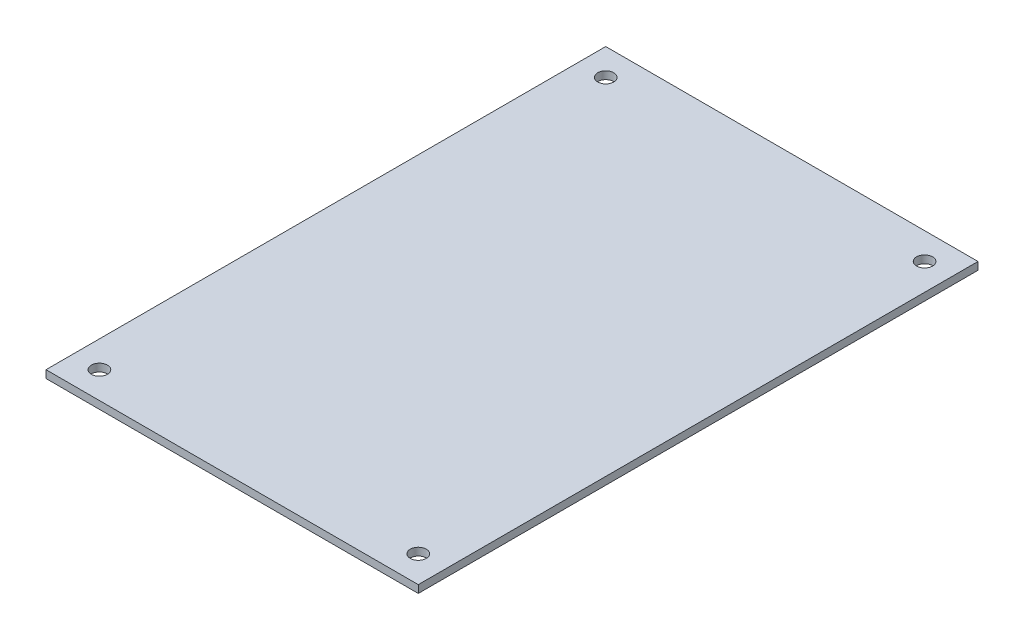
SolidWorks part; units mm, degrees
ref_plane "Front Plane" through (0, 0, 0) normal (0, 0, 1) x (1, 0, 0)
ref_plane "Top Plane" through (0, 0, 0) normal (0, 1, 0) x (1, 0, 0)
ref_plane "Right Plane" through (0, 0, 0) normal (1, 0, 0) x (0, 0, -1)
sketch "Sketch1" plane through (0, 0, 0) normal (0, 1, 0) x (1, 0, 0)
  line L1 (39.4716, -59.3471) -> (-39.4716, -59.3471)
  line L2 (39.4716, -59.3471) -> (39.4716, 59.3471)
  line L3 (39.4716, 59.3471) -> (-39.4716, 59.3471)
  line L4 (-39.4716, -59.3471) -> (-39.4716, 59.3471)
  line L5 (39.4716, -59.3471) -> (-39.4716, 59.3471) construction
  line L6 (39.4716, 59.3471) -> (-39.4716, -59.3471) construction
  point P0 (0, 0)
  dimension "D1" = 78.9432
  dimension "D2" = 118.6942
extrude "Boss-Extrude1" add sketch "Sketch1" along normal blind 1.6256
sketch "Sketch2" plane through (0, 1.6256, 0) normal (0, 1, 0) x (1, 0, 0)
  line L0 (-39.4716, 59.3471) -> (-39.4716, -59.3471) construction
  line L1 (39.4716, 59.3471) -> (-39.4716, 59.3471) construction
  circle A0 centre (-33.8074, 53.6829) radius 1.7018
  dimension "D1" = 3.4036
  dimension "D2" = 5.6642
  dimension "D3" = 5.6642
extrude "Cut-Extrude1" cut sketch "Sketch2" against normal up to next
mirror "Mirror1" about plane through (0, 0, 0) normal (1, 0, 0) of "Cut-Extrude1"
mirror "Mirror2" about plane through (0, 0, 0) normal (0, 0, 1) of "Mirror1", "Cut-Extrude1"
